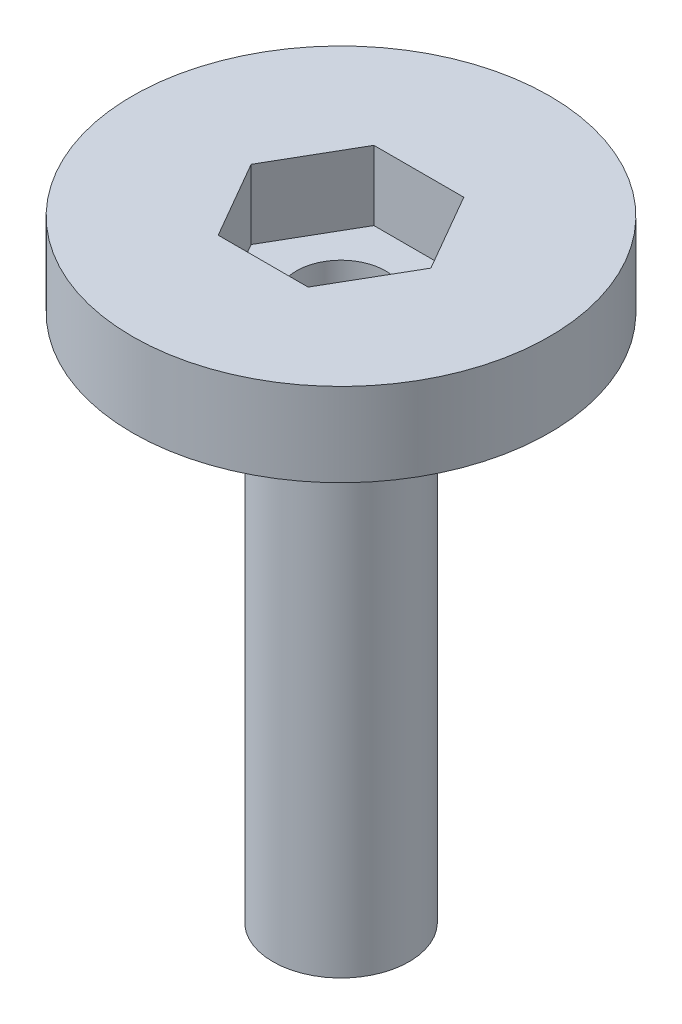
SolidWorks part; units mm, degrees
ref_plane "Front Plane" through (0, 0, 0) normal (0, 0, 1) x (1, 0, 0)
ref_plane "Top Plane" through (0, 0, 0) normal (0, 1, 0) x (1, 0, 0)
ref_plane "Right Plane" through (0, 0, 0) normal (1, 0, 0) x (0, 0, -1)
sketch "Sketch1" plane through (0, 0, 0) normal (0, 1, 0) x (1, 0, 0)
  circle A0 centre (0, 0) radius 2.45
  circle A1 centre (0, 0) radius 1.6
  dimension "D1" = 4.9
  dimension "D2" = 3.2
extrude "Boss-Extrude1" add sketch "Sketch1" along normal blind 19
sketch "Sketch2" plane through (0, 19, 0) normal (0, 1, 0) x (1, 0, 0)
  circle A0 centre (0, 0) radius 7.5
  dimension "D1" = 15
extrude "Boss-Extrude2" add sketch "Sketch2" along normal blind 3
sketch "Sketch3" plane through (0, 22, 0) normal (0, 1, 0) x (1, 0, 0)
  circle A0 centre (0, 0) radius 1.6
  dimension "D1" = 3.2
extrude "Cut-Extrude1" cut sketch "Sketch3" against normal up to next
sketch "Sketch4" plane through (0, 22, 0) normal (0, 1, 0) x (1, 0, 0)
  line L1 (3.2332, 0) -> (1.6166, 2.8)
  line L2 (1.6166, 2.8) -> (-1.6166, 2.8)
  line L3 (-1.6166, 2.8) -> (-3.2332, 0)
  line L4 (-3.2332, 0) -> (-1.6166, -2.8)
  line L5 (-1.6166, -2.8) -> (1.6166, -2.8)
  line L6 (1.6166, -2.8) -> (3.2332, 0)
  circle A0 centre (0, 0) radius 2.8 construction
  dimension "D1" = 5.6
extrude "Cut-Extrude2" cut sketch "Sketch4" against normal blind 2.5
